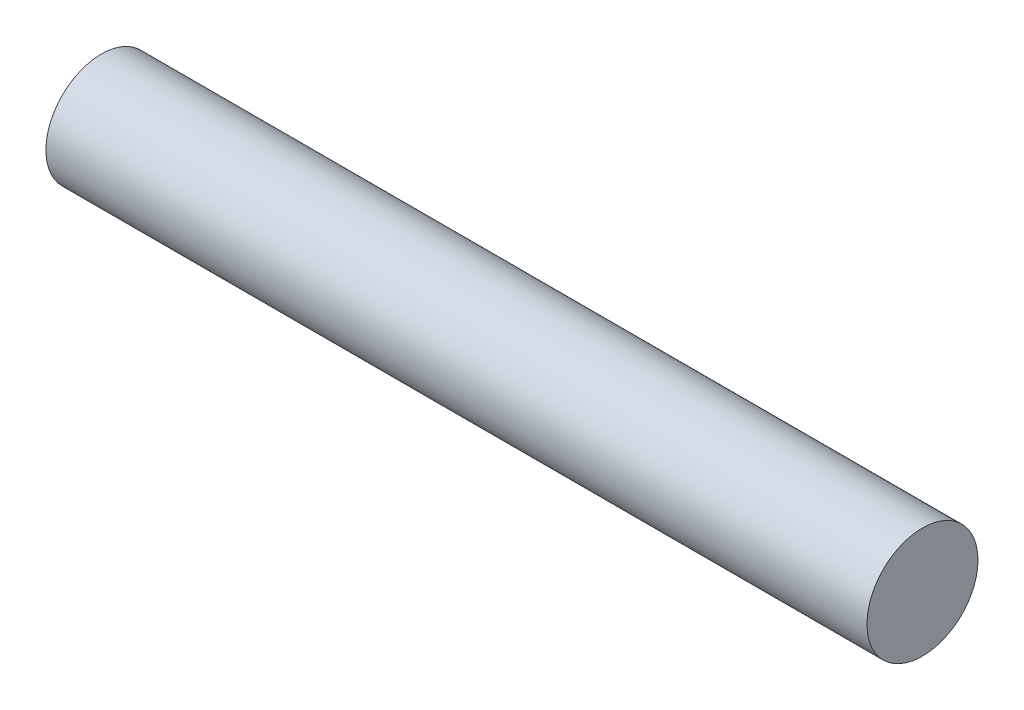
SolidWorks part; units mm, degrees
material "Brass"
ref_plane "Front Plane" through (0, 0, 0) normal (0, 0, 1) x (1, 0, 0)
ref_plane "Top Plane" through (0, 0, 0) normal (0, 1, 0) x (1, 0, 0)
ref_plane "Right Plane" through (0, 0, 0) normal (1, 0, 0) x (0, 0, -1)
sketch "Sketch1" plane through (0, 0, 0) normal (1, 0, 0) x (0, 0, -1)
  circle A0 centre (0, 0) radius 3.9688
  dimension "D1" = 7.9375
extrude "Boss-Extrude1" add sketch "Sketch1" along normal blind 58.674
